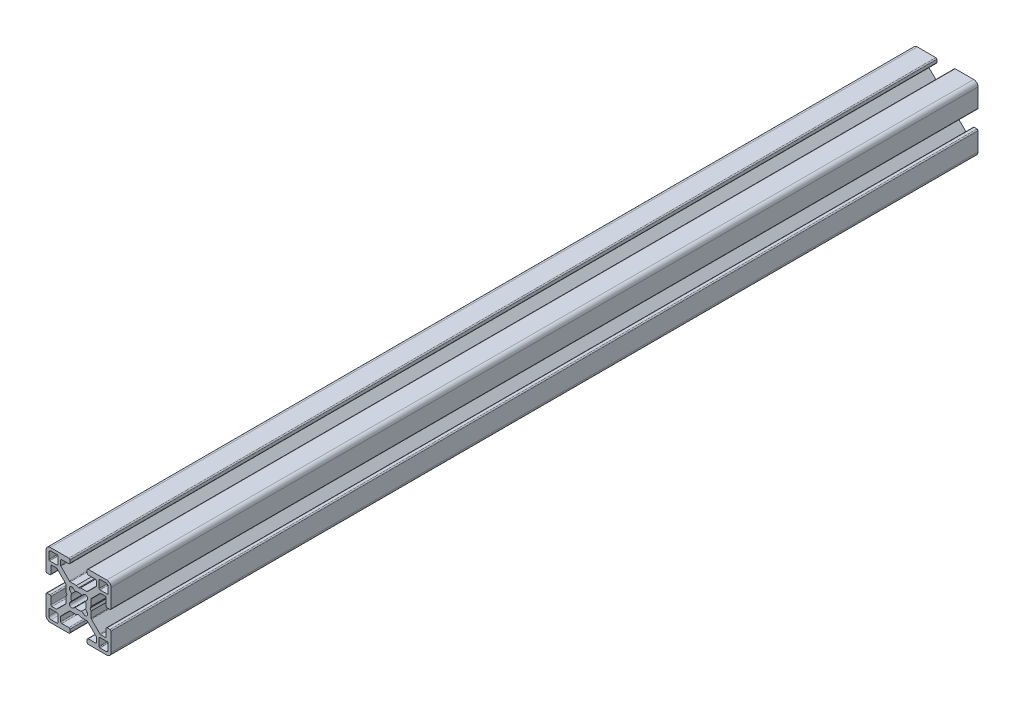
SolidWorks part; units mm, degrees
material "6105-T5 Aluminum"
ref_plane "Front Plane" through (0, 0, 0) normal (0, 0, 1) x (1, 0, 0)
ref_plane "Top Plane" through (0, 0, 0) normal (0, 1, 0) x (1, 0, 0)
ref_plane "Right Plane" through (0, 0, 0) normal (1, 0, 0) x (0, 0, -1)
sketch "Sketch1" plane through (0, 0, 0) normal (0, 0, 1) x (1, 0, 0)
  line L0 (9.5, -13.3189) -> (9.5, -9.88)
  line L1 (9.88, -9.5) -> (13.3189, -9.5)
  line L2 (13.6999, -9.881) -> (13.6999, -12.6999)
  line L3 (12.6999, -13.6999) -> (9.881, -13.6999)
  line L4 (-13.3189, -9.5) -> (-9.88, -9.5)
  line L5 (-9.5, -9.88) -> (-9.5, -13.3189)
  line L6 (-9.881, -13.6999) -> (-12.6999, -13.6999)
  line L7 (-13.6999, -12.6999) -> (-13.6999, -9.881)
  line L8 (-1.4942, -3.1981) -> (-2.4733, -3.9799)
  line L9 (-3.9799, -2.4733) -> (-3.1981, -1.4942)
  line L10 (-3.1981, 1.4942) -> (-3.9799, 2.4733)
  line L11 (-2.4733, 3.9799) -> (-1.4942, 3.1981)
  line L12 (1.4942, 3.1981) -> (2.4733, 3.9799)
  line L13 (3.9799, 2.4733) -> (3.1981, 1.4942)
  line L14 (3.1981, -1.4942) -> (3.9799, -2.4733)
  line L15 (2.4733, -3.9799) -> (1.4942, -3.1981)
  line L16 (-9.5, 13.3189) -> (-9.5, 9.88)
  line L17 (-9.88, 9.5) -> (-13.3189, 9.5)
  line L18 (-13.6999, 9.881) -> (-13.6999, 12.6999)
  line L19 (-12.6999, 13.6999) -> (-9.881, 13.6999)
  line L20 (9.881, 13.6999) -> (12.6999, 13.6999)
  line L21 (13.6999, 12.6999) -> (13.6999, 9.881)
  line L22 (13.3189, 9.5) -> (9.88, 9.5)
  line L23 (9.5, 9.88) -> (9.5, 13.3189)
  line L24 (12.7425, -4.5) -> (12.7425, -7.7325)
  line L25 (12.2428, -8.25) -> (10.2602, -8.25)
  line L26 (9.9066, -8.1035) -> (5.9811, -4.178)
  line L27 (5.8347, -3.8245) -> (5.8347, -1.0125)
  line L28 (5.8347, -1.0125) -> (5.3247, -0.0625)
  line L29 (5.3247, -0.0625) -> (5.8347, 0.8875)
  line L30 (5.8347, 0.8875) -> (5.8347, 3.8245)
  line L31 (5.9811, 4.178) -> (9.9066, 8.1035)
  line L32 (10.2602, 8.25) -> (12.2428, 8.25)
  line L33 (12.7425, 7.7325) -> (12.7425, 4.5)
  line L34 (13.2425, 4) -> (14.4999, 4)
  line L35 (14.9999, 4.5) -> (14.9999, 12.9999)
  line L36 (12.9999, 14.9999) -> (4.5, 14.9999)
  line L37 (4, 14.4999) -> (4, 13.2425)
  line L38 (4.5, 12.7425) -> (7.7325, 12.7425)
  line L39 (8.25, 12.2428) -> (8.25, 10.2602)
  line L40 (8.1035, 9.9066) -> (4.178, 5.9811)
  line L41 (3.8245, 5.8347) -> (0.95, 5.8347)
  line L42 (0.95, 5.8347) -> (0, 5.3247)
  line L43 (0, 5.3247) -> (-0.95, 5.8347)
  line L44 (-0.95, 5.8347) -> (-3.8245, 5.8347)
  line L45 (-4.178, 5.9811) -> (-8.1035, 9.9066)
  line L46 (-8.25, 10.2602) -> (-8.25, 12.2428)
  line L47 (-7.7325, 12.7425) -> (-4.5, 12.7425)
  line L48 (-4, 13.2425) -> (-4, 14.4999)
  line L49 (-4.5, 14.9999) -> (-12.9999, 14.9999)
  line L50 (-14.9999, 12.9999) -> (-14.9999, 4.5)
  line L51 (-14.4999, 4) -> (-13.2425, 4)
  line L52 (-12.7425, 4.5) -> (-12.7425, 7.7325)
  line L53 (-12.2428, 8.25) -> (-10.2602, 8.25)
  line L54 (-9.9066, 8.1035) -> (-5.9811, 4.178)
  line L55 (-5.8347, 3.8245) -> (-5.8347, 0.8875)
  line L56 (-5.8347, 0.8875) -> (-5.3247, -0.0625)
  line L57 (-5.3247, -0.0625) -> (-5.8347, -1.0125)
  line L58 (-5.8347, -1.0125) -> (-5.8347, -3.8245)
  line L59 (-5.9811, -4.178) -> (-9.9066, -8.1035)
  line L60 (-10.2602, -8.25) -> (-12.2428, -8.25)
  line L61 (-12.7425, -7.7325) -> (-12.7425, -4.5)
  line L62 (-13.2425, -4) -> (-14.4999, -4)
  line L63 (-14.9999, -4.5) -> (-14.9999, -12.9999)
  line L64 (-12.9999, -14.9999) -> (-4.5, -14.9999)
  line L65 (-4, -14.4999) -> (-4, -13.2425)
  line L66 (-4.5, -12.7425) -> (-7.7325, -12.7425)
  line L67 (-8.25, -12.2428) -> (-8.25, -10.2602)
  line L68 (-8.1035, -9.9066) -> (-4.178, -5.9811)
  line L69 (-3.8245, -5.8347) -> (-0.95, -5.8347)
  line L70 (-0.95, -5.8347) -> (0, -5.3247)
  line L71 (0, -5.3247) -> (0.95, -5.8347)
  line L72 (0.95, -5.8347) -> (3.8245, -5.8347)
  line L73 (4.178, -5.9811) -> (8.1035, -9.9066)
  line L74 (8.25, -10.2602) -> (8.25, -12.2428)
  line L75 (7.7325, -12.7425) -> (4.5, -12.7425)
  line L76 (4, -13.2425) -> (4, -14.4999)
  line L77 (4.5, -14.9999) -> (12.9999, -14.9999)
  line L78 (14.9999, -12.9999) -> (14.9999, -4.5)
  line L79 (14.4999, -4) -> (13.2425, -4)
  arc A0 (9.5, -13.3189) -> (9.881, -13.6999) centre (9.881, -13.3189) ccw
  arc A1 (9.88, -9.5) -> (9.5, -9.88) centre (9.88, -9.88) ccw
  arc A2 (13.6999, -9.881) -> (13.3189, -9.5) centre (13.3189, -9.881) ccw
  arc A3 (12.6999, -13.6999) -> (13.6999, -12.6999) centre (12.6999, -12.6999) ccw
  arc A4 (-13.3189, -9.5) -> (-13.6999, -9.881) centre (-13.3189, -9.881) ccw
  arc A5 (-9.5, -9.88) -> (-9.88, -9.5) centre (-9.88, -9.88) ccw
  arc A6 (-9.881, -13.6999) -> (-9.5, -13.3189) centre (-9.881, -13.3189) ccw
  arc A7 (-13.6999, -12.6999) -> (-12.6999, -13.6999) centre (-12.6999, -12.6999) ccw
  arc A8 (-1.4942, -3.1981) -> (1.4942, -3.1981) centre (0, 0) ccw
  arc A9 (-3.9799, -2.4733) -> (-2.4733, -3.9799) centre (-3.1422, -3.1422) ccw
  arc A10 (-3.1981, 1.4942) -> (-3.1981, -1.4942) centre (0, 0) ccw
  arc A11 (-2.4733, 3.9799) -> (-3.9799, 2.4733) centre (-3.1422, 3.1422) ccw
  arc A12 (1.4942, 3.1981) -> (-1.4942, 3.1981) centre (0, 0) ccw
  arc A13 (3.9799, 2.4733) -> (2.4733, 3.9799) centre (3.1422, 3.1422) ccw
  arc A14 (3.1981, -1.4942) -> (3.1981, 1.4942) centre (0, 0) ccw
  arc A15 (2.4733, -3.9799) -> (3.9799, -2.4733) centre (3.1422, -3.1422) ccw
  arc A16 (-9.5, 13.3189) -> (-9.881, 13.6999) centre (-9.881, 13.3189) ccw
  arc A17 (-9.88, 9.5) -> (-9.5, 9.88) centre (-9.88, 9.88) ccw
  arc A18 (-13.6999, 9.881) -> (-13.3189, 9.5) centre (-13.3189, 9.881) ccw
  arc A19 (-12.6999, 13.6999) -> (-13.6999, 12.6999) centre (-12.6999, 12.6999) ccw
  arc A20 (9.881, 13.6999) -> (9.5, 13.3189) centre (9.881, 13.3189) ccw
  arc A21 (13.6999, 12.6999) -> (12.6999, 13.6999) centre (12.6999, 12.6999) ccw
  arc A22 (13.3189, 9.5) -> (13.6999, 9.881) centre (13.3189, 9.881) ccw
  arc A23 (9.5, 9.88) -> (9.88, 9.5) centre (9.88, 9.88) ccw
  arc A24 (13.2425, -4) -> (12.7425, -4.5) centre (13.2425, -4.5) ccw
  arc A25 (12.2428, -8.25) -> (12.7425, -7.7325) centre (12.2428, -7.75) ccw
  arc A26 (9.9066, -8.1035) -> (10.2602, -8.25) centre (10.2602, -7.75) ccw
  arc A27 (5.8347, -3.8245) -> (5.9811, -4.178) centre (6.3347, -3.8245) ccw
  arc A28 (5.9811, 4.178) -> (5.8347, 3.8245) centre (6.3347, 3.8245) ccw
  arc A29 (10.2602, 8.25) -> (9.9066, 8.1035) centre (10.2602, 7.75) ccw
  arc A30 (12.7425, 7.7325) -> (12.2428, 8.25) centre (12.2428, 7.75) ccw
  arc A31 (12.7425, 4.5) -> (13.2425, 4) centre (13.2425, 4.5) ccw
  arc A32 (14.4999, 4) -> (14.9999, 4.5) centre (14.4999, 4.5) ccw
  arc A33 (14.9999, 12.9999) -> (12.9999, 14.9999) centre (12.9999, 12.9999) ccw
  arc A34 (4.5, 14.9999) -> (4, 14.4999) centre (4.5, 14.4999) ccw
  arc A35 (4, 13.2425) -> (4.5, 12.7425) centre (4.5, 13.2425) ccw
  arc A36 (8.25, 12.2428) -> (7.7325, 12.7425) centre (7.75, 12.2428) ccw
  arc A37 (8.1035, 9.9066) -> (8.25, 10.2602) centre (7.75, 10.2602) ccw
  arc A38 (3.8245, 5.8347) -> (4.178, 5.9811) centre (3.8245, 6.3347) ccw
  arc A39 (-4.178, 5.9811) -> (-3.8245, 5.8347) centre (-3.8245, 6.3347) ccw
  arc A40 (-8.25, 10.2602) -> (-8.1035, 9.9066) centre (-7.75, 10.2602) ccw
  arc A41 (-7.7325, 12.7425) -> (-8.25, 12.2428) centre (-7.75, 12.2428) ccw
  arc A42 (-4.5, 12.7425) -> (-4, 13.2425) centre (-4.5, 13.2425) ccw
  arc A43 (-4, 14.4999) -> (-4.5, 14.9999) centre (-4.5, 14.4999) ccw
  arc A44 (-12.9999, 14.9999) -> (-14.9999, 12.9999) centre (-12.9999, 12.9999) ccw
  arc A45 (-14.9999, 4.5) -> (-14.4999, 4) centre (-14.4999, 4.5) ccw
  arc A46 (-13.2425, 4) -> (-12.7425, 4.5) centre (-13.2425, 4.5) ccw
  arc A47 (-12.2428, 8.25) -> (-12.7425, 7.7325) centre (-12.2428, 7.75) ccw
  arc A48 (-9.9066, 8.1035) -> (-10.2602, 8.25) centre (-10.2602, 7.75) ccw
  arc A49 (-5.8347, 3.8245) -> (-5.9811, 4.178) centre (-6.3347, 3.8245) ccw
  arc A50 (-5.9811, -4.178) -> (-5.8347, -3.8245) centre (-6.3347, -3.8245) ccw
  arc A51 (-10.2602, -8.25) -> (-9.9066, -8.1035) centre (-10.2602, -7.75) ccw
  arc A52 (-12.7425, -7.7325) -> (-12.2428, -8.25) centre (-12.2428, -7.75) ccw
  arc A53 (-12.7425, -4.5) -> (-13.2425, -4) centre (-13.2425, -4.5) ccw
  arc A54 (-14.4999, -4) -> (-14.9999, -4.5) centre (-14.4999, -4.5) ccw
  arc A55 (-14.9999, -12.9999) -> (-12.9999, -14.9999) centre (-12.9999, -12.9999) ccw
  arc A56 (-4.5, -14.9999) -> (-4, -14.4999) centre (-4.5, -14.4999) ccw
  arc A57 (-4, -13.2425) -> (-4.5, -12.7425) centre (-4.5, -13.2425) ccw
  arc A58 (-8.25, -12.2428) -> (-7.7325, -12.7425) centre (-7.75, -12.2428) ccw
  arc A59 (-8.1035, -9.9066) -> (-8.25, -10.2602) centre (-7.75, -10.2602) ccw
  arc A60 (-3.8245, -5.8347) -> (-4.178, -5.9811) centre (-3.8245, -6.3347) ccw
  arc A61 (4.178, -5.9811) -> (3.8245, -5.8347) centre (3.8245, -6.3347) ccw
  arc A62 (8.25, -10.2602) -> (8.1035, -9.9066) centre (7.75, -10.2602) ccw
  arc A63 (7.7325, -12.7425) -> (8.25, -12.2428) centre (7.75, -12.2428) ccw
  arc A64 (4.5, -12.7425) -> (4, -13.2425) centre (4.5, -13.2425) ccw
  arc A65 (4, -14.4999) -> (4.5, -14.9999) centre (4.5, -14.4999) ccw
  arc A66 (12.9999, -14.9999) -> (14.9999, -12.9999) centre (12.9999, -12.9999) ccw
  arc A67 (14.9999, -4.5) -> (14.4999, -4) centre (14.4999, -4.5) ccw
extrude "Extrude1" add sketch "Sketch1" against normal blind 400
